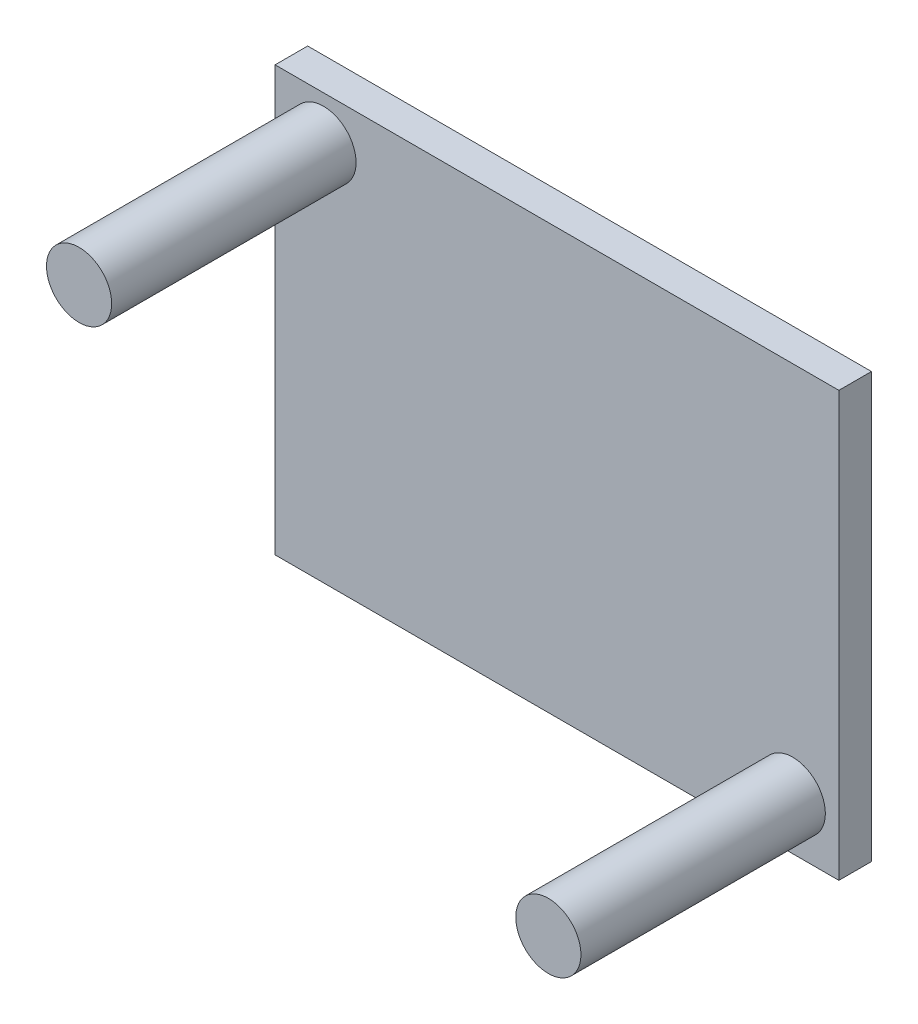
SolidWorks part; units mm, degrees
ref_plane "Front Plane" through (0, 0, 0) normal (0, 0, 1) x (1, 0, 0)
ref_plane "Top Plane" through (0, 0, 0) normal (0, 1, 0) x (1, 0, 0)
ref_plane "Right Plane" through (0, 0, 0) normal (1, 0, 0) x (0, 0, -1)
sketch "Sketch1" plane through (0, 0, 0) normal (0, 0, 1) x (1, 0, 0)
  circle A0 centre (0, 0) radius 2
  circle A1 centre (28.8, -20.2) radius 2
  dimension "D2" = 4
  dimension "D1" = 28.8
  dimension "D3" = 20.2
extrude "Boss-Extrude1" add sketch "Sketch1" along normal blind 15
sketch "Sketch2" plane through (0, 0, 0) normal (0, 0, 1) x (1, 0, 0)
  line L1 (-2.9699, 2.7127) -> (31.6297, 2.7127)
  line L2 (-2.9699, 2.7127) -> (-2.9699, -23.3334)
  line L3 (-2.9699, -23.3334) -> (31.6297, -23.3334)
  line L4 (31.6297, 2.7127) -> (31.6297, -23.3334)
extrude "Boss-Extrude2" add sketch "Sketch2" against normal blind 2
